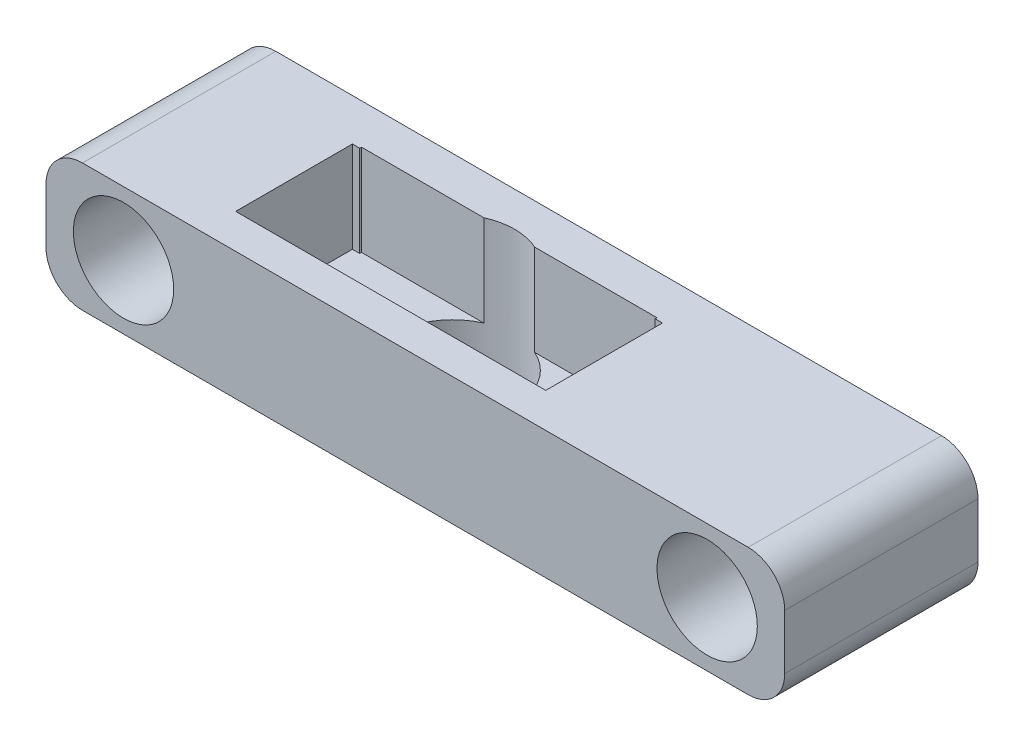
SolidWorks part; units mm, degrees
ref_plane "Alzado" through (0, 0, 0) normal (0, 0, 1) x (1, 0, 0)
ref_plane "Planta" through (0, 0, 0) normal (0, 1, 0) x (1, 0, 0)
ref_plane "Vista lateral" through (0, 0, 0) normal (1, 0, 0) x (0, 0, -1)
sketch "Croquis1" plane through (0, 0, 0) normal (0, 0, 1) x (1, 0, 0)
  line L1 (-46.433, -7.2866) -> (-5.933, -7.2866)
  line L2 (-46.433, -7.2866) -> (-46.433, -14.2866)
  line L3 (-46.433, -14.2866) -> (-5.933, -14.2866)
  line L4 (-5.933, -7.2866) -> (-5.933, -14.2866)
  circle A0 centre (-42.183, -10.7866) radius 2.75
  circle A1 centre (-10.183, -10.7866) radius 2.75
  dimension "D5" = 2
  dimension "D6" = 4.25
  dimension "D8" = 5.5
  dimension "D1" = 3.5
  dimension "D2" = 7
  dimension "D3" = 4.25
  dimension "D4" = 3.5
  dimension "D7" = 32
extrude "Saliente-Extruir1" add sketch "Croquis1" along normal blind 10.6
sketch "Croquis4" plane through (0, -14.2866, 0) normal (0, -1, 0) x (1, 0, 0)
  line L0 (-34.225, 5.3) -> (-34.8087, 5.3) construction
  line L1 (-24.641, 5.3) -> (-27.037, 9.45)
  line L2 (-27.037, 9.45) -> (-31.829, 9.45)
  line L3 (-31.829, 9.45) -> (-34.225, 5.3)
  line L4 (-34.225, 5.3) -> (-31.829, 1.15)
  line L5 (-31.829, 1.15) -> (-27.037, 1.15)
  line L6 (-27.037, 1.15) -> (-24.641, 5.3)
  line L7 (-46.433, 10.6) -> (-46.433, 0) construction
  line L8 (-46.433, 10.6) -> (-5.933, 10.6) construction
  circle A0 centre (-29.433, 5.3) radius 3.25
  circle A1 centre (-29.433, 5.3) radius 4.15 construction
  dimension "D1" = 17
  dimension "D2" = 8.3
  dimension "D3" = 1.15
sketch "Croquis5" plane through (0, -14.2866, 0) normal (0, -1, 0) x (1, 0, 0)
  circle A0 centre (-29.433, 5.3) radius 3.4
extrude "Cortar-Extruir4" cut sketch "Croquis5" against normal up to vertex (7 mm away)
fillet "Redondeo1" radius 2 4 edges at (-5.933, -7.2866, 5.3) (-5.933, -14.2866, 5.3) (-46.433, -14.2866, 5.3) (-46.433, -7.2866, 5.3)
sketch "Croquis7" plane through (0, -7.2866, 0) normal (0, 1, 0) x (1, 0, 0)
  line L0 (-29.433, -5.3) -> (-29.433, -8.7) construction
  line L1 (-29.433, -8.7) -> (-20.933, -8.7) construction
  line L2 (-20.933, -8.7) -> (-20.933, -2.3) construction
  line L3 (-20.933, -2.3) -> (-37.933, -2.3) construction
  line L4 (-37.933, -2.3) -> (-37.933, -8.7) construction
  line L5 (-37.933, -8.7) -> (-29.433, -8.7) construction
  line L6 (-20.933, -8.7) -> (-20.933, -2.3)
  line L7 (-20.933, -2.3) -> (-37.933, -2.3)
  line L8 (-37.933, -2.3) -> (-37.933, -8.7)
  line L9 (-37.933, -8.7) -> (-20.933, -8.7)
  circle A0 centre (-29.433, -5.3) radius 3.4 construction
  dimension "D1" = 17
  dimension "D2" = 6.4
  dimension "D3" = 8.5
extrude "Cortar-Extruir5" cut sketch "Croquis7" against normal blind 5
sketch "Croquis8" plane through (0, -12.2866, 0) normal (0, 1, 0) x (1, 0, 0)
  line L0 (-20.933, -8.7) -> (-20.933, -2.3) construction
  line L1 (-37.933, -2.3) -> (-37.933, -8.7) construction
  line L2 (-20.933, -2.3) -> (-27.833, -2.3) construction
  line L4 (-31.033, -2.3) -> (-37.933, -2.3) construction
  circle A0 centre (-22.933, -5.5) radius 1.5
  circle A1 centre (-35.933, -5.5) radius 1.5
  dimension "D2" = 3
  dimension "D3" = 2
  dimension "D1" = 2
  dimension "D4" = 3.2
  dimension "D5" = 3.2
extrude "Cortar-Extruir6" cut sketch "Croquis8" against normal up to vertex (2 mm away)
sketch "Croquis9" plane through (0, -7.2866, 0) normal (0, 1, 0) x (1, 0, 0)
  line L1 (-21.333, -2.2) -> (-37.533, -2.2)
  line L2 (-21.333, -2.2) -> (-21.333, -8.4)
  line L3 (-21.333, -8.4) -> (-37.533, -8.4)
  line L4 (-37.533, -2.2) -> (-37.533, -8.4)
  line L5 (-21.333, -2.2) -> (-37.533, -8.4) construction
  line L6 (-21.333, -8.4) -> (-37.533, -2.2) construction
  point P0 (-29.433, -5.3)
  dimension "D1" = 6.2
  dimension "D2" = 16.2
extrude "Cortar-Extruir7" cut sketch "Croquis9" against normal up to vertex (5 mm away)
